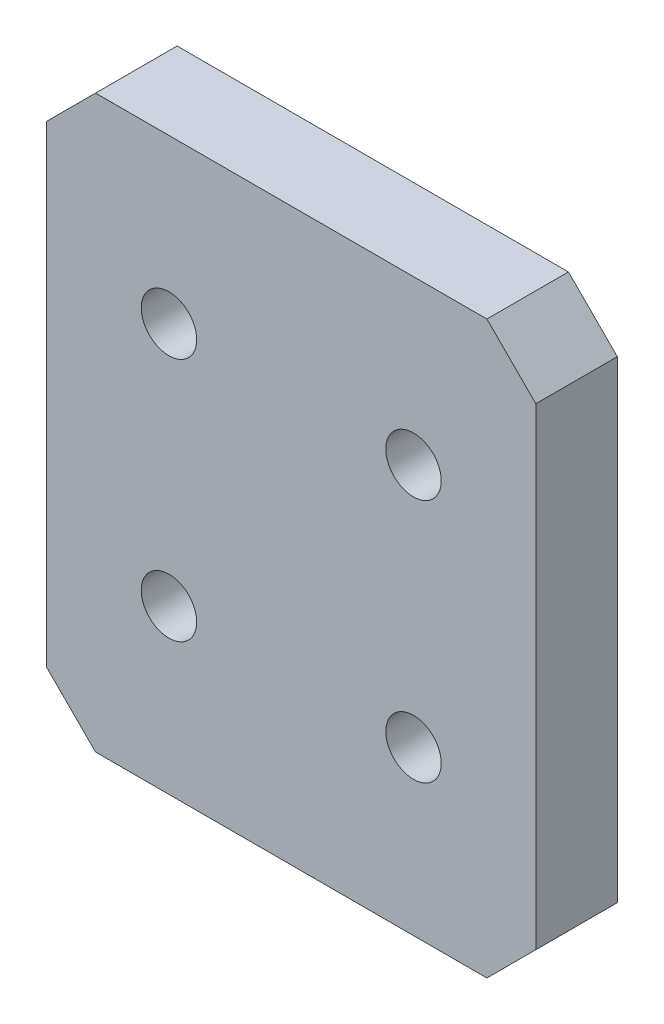
SolidWorks part; units mm, degrees
material "5052-O"
ref_plane "Front Plane" through (0, 0, 0) normal (0, 0, 1) x (1, 0, 0)
ref_plane "Top Plane" through (0, 0, 0) normal (0, 1, 0) x (1, 0, 0)
ref_plane "Right Plane" through (0, 0, 0) normal (1, 0, 0) x (0, 0, -1)
sketch "Sketch1" plane through (0, 0, 0) normal (0, 0, 1) x (1, 0, 0)
  line L1 (-15, 17.5) -> (15, 17.5)
  line L2 (-15, 17.5) -> (-15, -17.5)
  line L3 (-15, -17.5) -> (15, -17.5)
  line L4 (15, 17.5) -> (15, -17.5)
  line L5 (-15, 17.5) -> (15, -17.5) construction
  line L6 (-15, -17.5) -> (15, 17.5) construction
  point P0 (0, 0)
  dimension "D1" = 30
  dimension "D2" = 35
extrude "Boss-Extrude1" add sketch "Sketch1" along normal blind 5
hole_wizard "M3 Clearance Hole1" positions "Sketch2" profile "Sketch3" hole size "M3" standard "ANSI Metric" end condition through all
sketch "Sketch2" plane through (0, 0, 5) normal (0, 0, 1) x (1, 0, 0)
  line L1 (-7.5, 7.5) -> (7.5, 7.5)
  line L2 (-7.5, 7.5) -> (-7.5, -7.5)
  line L3 (-7.5, -7.5) -> (7.5, -7.5)
  line L4 (7.5, 7.5) -> (7.5, -7.5)
  line L5 (-7.5, 7.5) -> (7.5, -7.5) construction
  line L6 (-7.5, -7.5) -> (7.5, 7.5) construction
  point P2 (7.5, -7.5)
  point P27 (-7.5, 7.5)
  point P28 (-7.5, -7.5)
  point P29 (7.5, 7.5)
  dimension "D1" = 15
  dimension "D2" = 15
sketch "Sketch3" plane through (7.5, -7.5, 5) normal (1, 0, 0) x (0, -1, 0)
  line L0 (0, 0) -> (0, 5)
  line L1 (0, 5) -> (1.7, 5)
  line L2 (1.7, 5) -> (1.7, 0)
  line L5 (1.7, 0) -> (0, 0)
  line L11 (0, -6.35) -> (0, 107.95) construction
  dimension "Thru Hole Dia." = 3.4
  dimension "Thru Hole Depth" = 5
chamfer "Chamfer1" distance 3 angle 45 4 edges at (15, 17.5, 2.5) (15, -17.5, 2.5) (-15, -17.5, 2.5) (-15, 17.5, 2.5)
